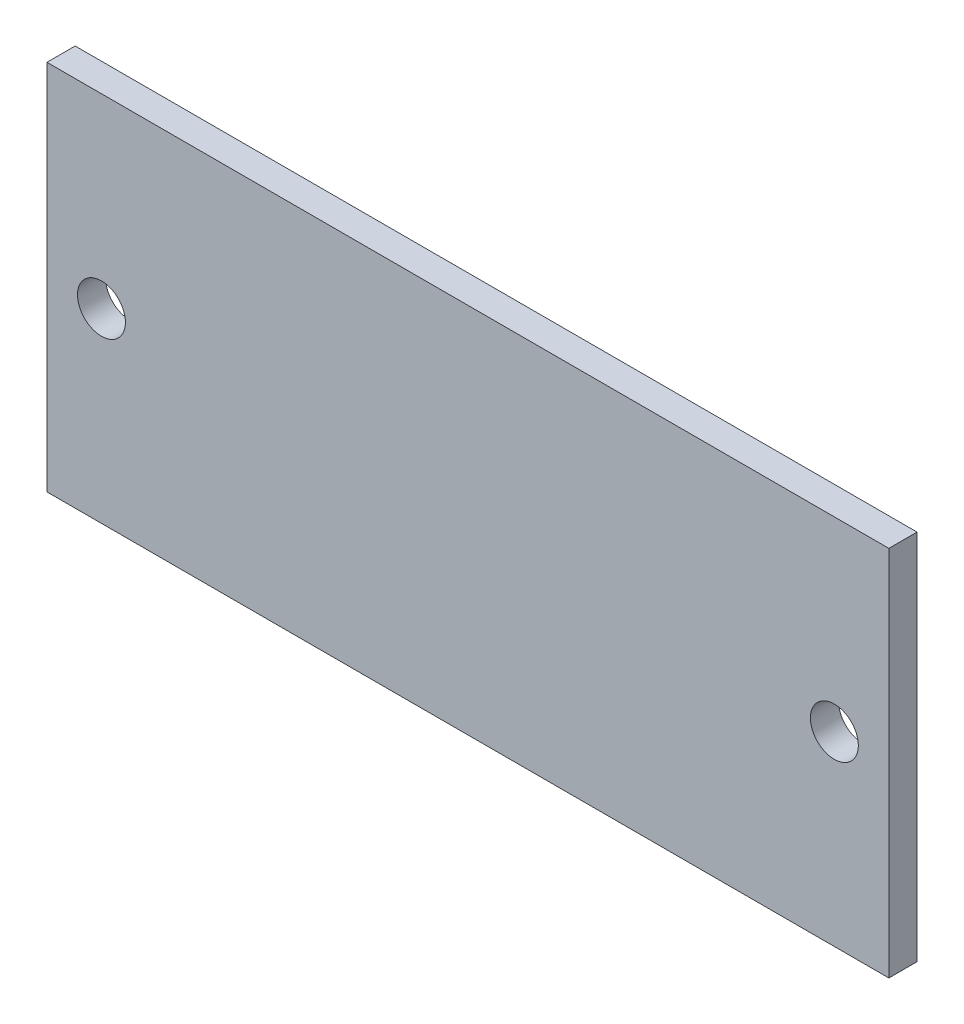
SolidWorks part; units mm, degrees
ref_plane "Front Plane" through (0, 0, 0) normal (0, 0, 1) x (1, 0, 0)
ref_plane "Top Plane" through (0, 0, 0) normal (0, 1, 0) x (1, 0, 0)
ref_plane "Right Plane" through (0, 0, 0) normal (1, 0, 0) x (0, 0, -1)
sketch "Sketch2" plane through (0, 0, 0) normal (0, 0, 1) x (1, 0, 0)
  line L1 (-22.4, 9.9) -> (22.4, 9.9)
  line L2 (-22.4, 9.9) -> (-22.4, -9.9)
  line L3 (-22.4, -9.9) -> (22.4, -9.9)
  line L4 (22.4, 9.9) -> (22.4, -9.9)
  line L5 (-22.4, 9.9) -> (22.4, -9.9) construction
  line L6 (-22.4, -9.9) -> (22.4, 9.9) construction
  point P0 (0, 0)
  dimension "D1" = 19.8
  dimension "D2" = 44.8
extrude "Boss-Extrude1" add sketch "Sketch2" along normal blind 1.5
sketch "Sketch3" plane through (0, 0, 1.5) normal (0, 0, 1) x (1, 0, 0)
  circle A0 centre (-19.5, 0) radius 1.275
  dimension "D1" = 2.55
  dimension "D2" = 19.5
extrude "Cut-Extrude1" cut sketch "Sketch3" against normal through all
mirror "Mirror1" about plane through (0, 0, 0) normal (1, 0, 0) of "Cut-Extrude1"
